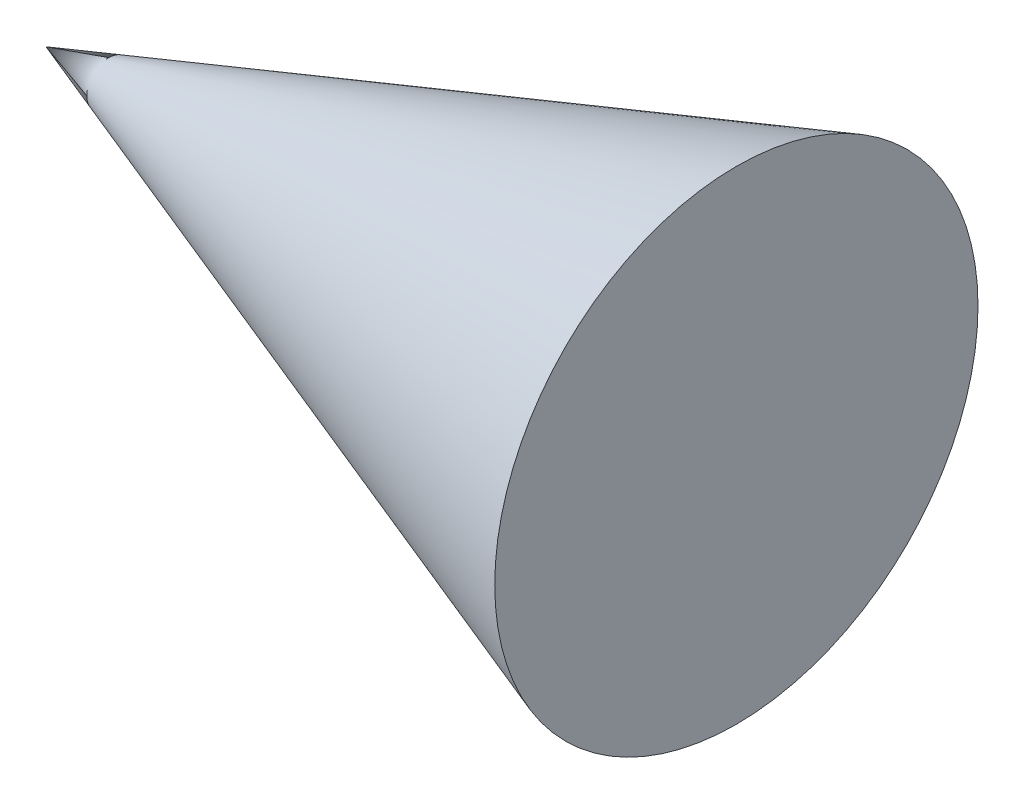
SolidWorks part; units mm, degrees
ref_plane "Front Plane" through (0, 0, 0) normal (0, 0, 1) x (1, 0, 0)
ref_plane "Top Plane" through (0, 0, 0) normal (0, 1, 0) x (1, 0, 0)
ref_plane "Right Plane" through (0, 0, 0) normal (1, 0, 0) x (0, 0, -1)
sketch "Sketch1" plane through (0, 0, 0) normal (0, 0, 1) x (1, 0, 0)
  line L0 (0, 0) -> (20, 7)
  line L1 (0, 0) -> (20, 0)
  line L2 (20, 0) -> (20, 7)
  dimension "D1" = 20
  dimension "D2" = 7
revolve "Revolve1" add sketch "Sketch1" angle 360 about L1
